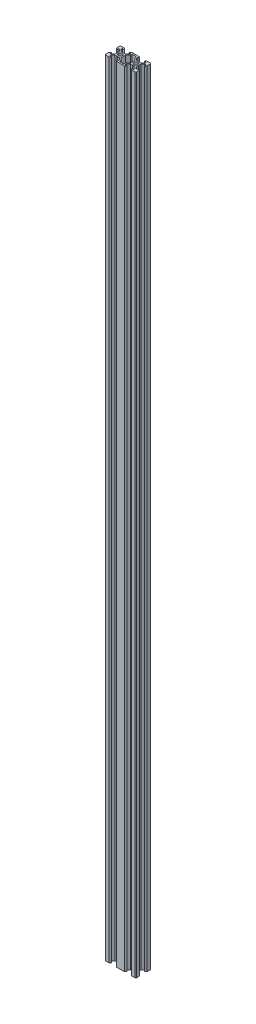
SolidWorks part; units mm, degrees
material "6063-T5"
material "6063-T5"
ref_plane "Plano frontal" through (0, 0, 0) normal (0, 0, 1) x (1, 0, 0)
ref_plane "Plano superior" through (0, 0, 0) normal (0, 1, 0) x (1, 0, 0)
ref_plane "Plano direito" through (0, 0, 0) normal (1, 0, 0) x (0, 0, -1)
sketch "Esboço1" plane through (0, 0, 0) normal (0, 0, 1) x (1, 0, 0)
  line L0 (0, 0) -> (0, 1020)
  dimension "D1" = 1020
other "Retangular PF20-12 - PERFIL 2040 V-SLOT(1)"
ref_plane "Plano1" through (0, 0, 0) normal (0, 1, 0) x (-1, 0, 0)
sketch "Sketch13" plane through (0, 0, 0) normal (0, 1, 0) x (-1, 0, 0)
  line L0 (-14.8, 10) -> (-13, 8.2)
  line L1 (-13, 8.2) -> (-15.5, 8.2)
  line L2 (-15.5, 8.2) -> (-15.5, 6.5607)
  line L3 (-15.5, 6.5607) -> (-12.9393, 4)
  line L4 (-12.9393, 4) -> (-10.3, 4)
  line L5 (-4.5, 6.5607) -> (-7.0607, 4)
  line L6 (-4.5, 8.2) -> (-4.5, 6.5607)
  line L7 (-7, 8.2) -> (-4.5, 8.2)
  line L8 (-5.2, 10) -> (-7, 8.2)
  line L9 (-10.3, 4) -> (-10, 3.7)
  line L10 (-9.7, 4) -> (-10, 3.7)
  line L11 (-9.7, 4) -> (-7.0607, 4)
  line L12 (-2.7, 8.2) -> (-2.7, 6.2393)
  line L13 (-2.7, 6.2393) -> (-6, 2.9393)
  line L14 (-2.7, 8.2) -> (2.7, 8.2)
  line L15 (2.7, 6.2393) -> (6, 2.9393)
  line L16 (2.7, 8.2) -> (2.7, 6.2393)
  line L17 (-5.2, -10) -> (5.2, -10)
  line L18 (-5.2, -10) -> (-7, -8.2)
  line L19 (-7, -8.2) -> (-4.5, -8.2)
  line L20 (-4.5, -8.2) -> (-4.5, -6.5607)
  line L21 (-4.5, -6.5607) -> (-7.0607, -4)
  line L22 (-7.0607, -4) -> (-9.7, -4)
  line L23 (-9.7, -4) -> (-10, -3.7)
  line L24 (-10.3, -4) -> (-10, -3.7)
  line L25 (-10.3, -4) -> (-12.9393, -4)
  line L26 (-15.5, -6.5607) -> (-12.9393, -4)
  line L27 (-15.5, -8.2) -> (-15.5, -6.5607)
  line L28 (-13, -8.2) -> (-15.5, -8.2)
  line L29 (-14.8, -10) -> (-13, -8.2)
  line L30 (-20, -4.8) -> (-20, -9)
  line L31 (-20, -4.8) -> (-18.2, -3)
  line L32 (-18.2, -3) -> (-18.2, -5.5)
  line L33 (-18.2, -5.5) -> (-16.5607, -5.5)
  line L34 (-16.5607, -5.5) -> (-14, -2.9393)
  line L35 (-14, -2.9393) -> (-14, -0.3)
  line L36 (-14, -0.3) -> (-13.7, 0)
  line L37 (-14, 0.3) -> (-13.7, 0)
  line L38 (-14, 0.3) -> (-14, 2.9393)
  line L39 (-16.5607, 5.5) -> (-14, 2.9393)
  line L40 (-18.2, 5.5) -> (-16.5607, 5.5)
  line L41 (-18.2, 3) -> (-18.2, 5.5)
  line L42 (-20, 4.8) -> (-18.2, 3)
  line L43 (-14.8, 10) -> (-19, 10)
  line L56 (5.2, 10) -> (-5.2, 10)
  line L57 (5.2, 10) -> (7, 8.2)
  line L58 (7, 8.2) -> (4.5, 8.2)
  line L59 (4.5, 8.2) -> (4.5, 6.5607)
  line L60 (4.5, 6.5607) -> (7.0607, 4)
  line L61 (9.7, 4) -> (7.0607, 4)
  line L62 (9.7, 4) -> (10, 3.7)
  line L63 (10.3, 4) -> (10, 3.7)
  line L64 (12.9393, 4) -> (10.3, 4)
  line L65 (15.5, 6.5607) -> (12.9393, 4)
  line L66 (15.5, 8.2) -> (15.5, 6.5607)
  line L67 (13, 8.2) -> (15.5, 8.2)
  line L68 (14.8, 10) -> (13, 8.2)
  line L69 (20, 4.8) -> (18.2, 3)
  line L70 (18.2, 3) -> (18.2, 5.5)
  line L71 (18.2, 5.5) -> (16.5607, 5.5)
  line L72 (16.5607, 5.5) -> (14, 2.9393)
  line L73 (14, 0.3) -> (14, 2.9393)
  line L74 (14, 0.3) -> (13.7, 0)
  line L75 (14, -0.3) -> (13.7, 0)
  line L76 (14, -2.9393) -> (14, -0.3)
  line L77 (16.5607, -5.5) -> (14, -2.9393)
  line L78 (18.2, -5.5) -> (16.5607, -5.5)
  line L79 (18.2, -3) -> (18.2, -5.5)
  line L80 (20, -4.8) -> (18.2, -3)
  line L81 (20, -9) -> (20, -4.8)
  line L82 (14.8, -10) -> (13, -8.2)
  line L83 (13, -8.2) -> (15.5, -8.2)
  line L84 (15.5, -8.2) -> (15.5, -6.5607)
  line L85 (15.5, -6.5607) -> (12.9393, -4)
  line L86 (10.3, -4) -> (12.9393, -4)
  line L87 (10.3, -4) -> (10, -3.7)
  line L88 (9.7, -4) -> (10, -3.7)
  line L89 (7.0607, -4) -> (9.7, -4)
  line L90 (4.5, -6.5607) -> (7.0607, -4)
  line L91 (4.5, -8.2) -> (4.5, -6.5607)
  line L92 (7, -8.2) -> (4.5, -8.2)
  line L93 (5.2, -10) -> (7, -8.2)
  line L99 (-6, 2.9393) -> (-6, -2.9393)
  line L100 (-2.7, -6.2393) -> (-6, -2.9393)
  line L101 (-2.7, -8.2) -> (-2.7, -6.2393)
  line L102 (-2.7, -8.2) -> (2.7, -8.2)
  line L103 (2.7, -8.2) -> (2.7, -6.2393)
  line L104 (2.7, -6.2393) -> (6, -2.9393)
  line L105 (6, 2.9393) -> (6, -2.9393)
  line L106 (-20, 9) -> (-20, 4.8)
  line L107 (-19, -10) -> (-14.8, -10)
  line L108 (19, 10) -> (14.8, 10)
  line L109 (20, 4.8) -> (20, 9)
  line L110 (14.8, -10) -> (19, -10)
  arc A3 (-20, -9) -> (-19, -10) centre (-19, -9) ccw
  arc A4 (-19, 10) -> (-20, 9) centre (-19, 9) ccw
  arc A5 (20, 9) -> (19, 10) centre (19, 9) ccw
  arc A6 (19, -10) -> (20, -9) centre (19, -9) ccw
  circle A7 centre (-10, 0) radius 2.5
  circle A8 centre (10, 0) radius 2.5
  point P1 (-20, 10)
  point P2 (20, 10)
  point P4 (20, 0)
  point P108 (0, 10)
  point P109 (0, 0)
  point P111 (20, -10)
  point P112 (10, -10)
  point P113 (-10, -10)
  point P114 (-20, -10)
  point P115 (-20, 0)
  point P116 (-10, 10)
  point P117 (10, 10)
  point P118 (-10, 0)
  point P119 (10, 0)
  point P120 (0, -10)
  point P121 (0, 0)
